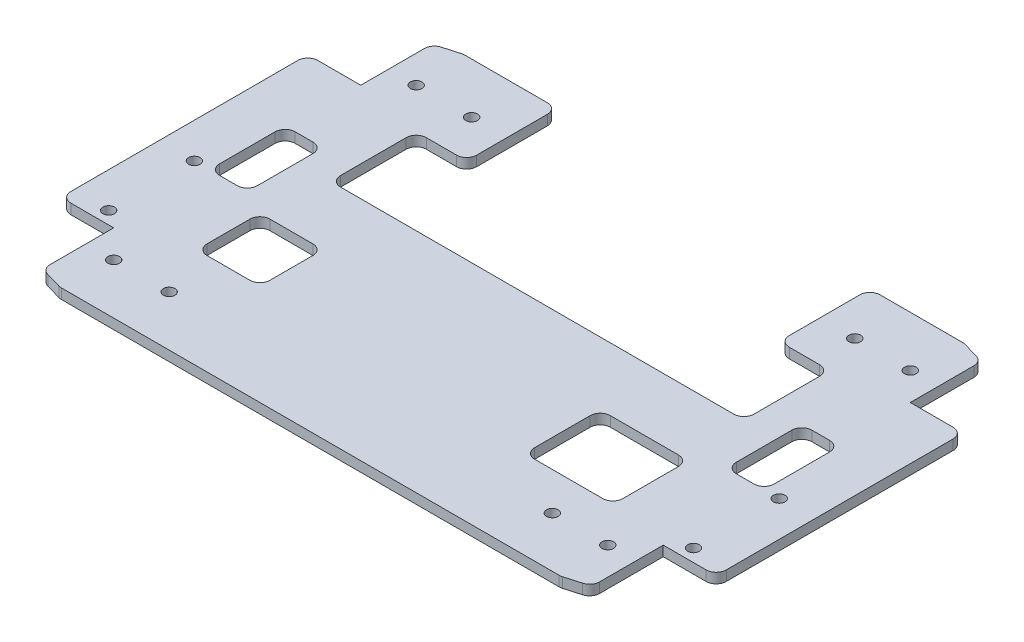
SolidWorks part; units mm, degrees
ref_plane "Plan de face" through (0, 0, 0) normal (0, 0, 1) x (1, 0, 0)
ref_plane "Plan de dessus" through (0, 0, 0) normal (0, 1, 0) x (1, 0, 0)
ref_plane "Plan de droite" through (0, 0, 0) normal (1, 0, 0) x (0, 0, -1)
sketch "Esquisse1" plane through (0, 0, 0) normal (0, 1, 0) x (1, 0, 0)
  line L0 (0, 0) -> (135, 0) construction
  line L1 (0, 0) -> (-135, 0) construction
  line L2 (-135, 0) -> (-135, -75)
  line L3 (-135, -85) -> (135, -85) construction
  line L4 (135, 0) -> (135, 75)
  line L5 (0, 85) -> (0, -85) construction
  line L6 (135, 85) -> (-135, 85) construction
  line L24 (0, -85) -> (-100, -85)
  line L26 (0, -85) -> (100, -85)
  line L28 (135, 0) -> (135, -75)
  line L31 (0, 85) -> (-100, 85)
  line L32 (0, 85) -> (100, 85)
  line L34 (-135, 0) -> (-135, 75)
  line L35 (-135, -75) -> (-100, -85)
  line L37 (-135, 75) -> (-100, 85)
  line L38 (100, 85) -> (135, 75)
  line L39 (100, -85) -> (135, -75)
  line L40 (-135, 75) -> (-100, 75) construction
  line L41 (-100, 75) -> (-100, 85) construction
  line L42 (100, -85) -> (135, -85) construction
  dimension "D2" = 270
  dimension "D4" = 200
  dimension "D8" = 170
extrude "Boss.-Extru.1" add sketch "Esquisse1" along normal blind 4
sketch "Esquisse15" plane through (0, 4, 0) normal (0, 1, 0) x (1, 0, 0)
  line L0 (-135, 60) -> (-135, 75)
  line L1 (-135, 60) -> (-120, 60) construction
  line L2 (-135, -60) -> (-120, -60) construction
  line L4 (-135, -60) -> (-135, -75)
  line L5 (-100, 85) -> (-135, 75) construction
  line L6 (-135, 75) -> (-135, -75) construction
  circle A0 centre (-120, 60) radius 2.3
  circle A1 centre (-120, -60) radius 2.3
extrude "Enlèv. mat.-Extru.6" cut sketch "Esquisse15" against normal up to next contours A1 | A0
mirror "Symétrie5" about plane through (0, 0, 0) normal (1, 0, 0) of "Enlèv. mat.-Extru.6"
sketch "Esquisse20" plane through (0, 4, 0) normal (0, 1, 0) x (1, 0, 0)
  line L0 (-120, -60) -> (-109, -60) construction
  line L1 (-109, -60) -> (-109, -82.4286)
  line L2 (-135, -75) -> (-100, -85) construction
  line L3 (-109, -60) -> (-109, -49)
  line L4 (-109, -49) -> (-135, -49)
  line L5 (-135, 75) -> (-135, -75) construction
  line L8 (-135, -49) -> (-135, -75)
  line L9 (-135, -75) -> (-109, -82.4286)
  line M49 (-135, 75) -> (-135, -75)
  line M50 (-135, -75) -> (-100, -85)
extrude "Enlèv. mat.-Extru.10" cut sketch "Esquisse20" against normal up to next contours L9 M49 M50
mirror "Symétrie7" about plane through (0, 0, 0) normal (1, 0, 0) of "Enlèv. mat.-Extru.10"
mirror "Symétrie8" about plane through (0, 0, 0) normal (0, 0, 1) of "Symétrie7", "Enlèv. mat.-Extru.10"
sketch "Esquisse26" plane through (0, 4, 0) normal (0, 1, 0) x (1, 0, 0)
  line L9 (-109, -82.4286) -> (-100, -85)
  line L14 (-100, -85) -> (-98.6264, -80.1924)
  line L16 (-109, -82.4286) -> (-107.6264, -77.621)
  line L17 (100, -85) -> (100, -80)
  line L18 (-107.6264, -77.621) -> (-98.6264, -80.1924)
  line L23 (-100, -85) -> (-100, -80)
  line L25 (-100, -80) -> (100, -80)
  line L34 (-135, -49) -> (-130, -49)
  line L35 (-109, -49) -> (-135, -49) construction
  line L47 (-107.6264, -77.621) -> (-109, -77.2285)
  line L48 (-109, -77.2285) -> (-109, -82.4286)
  line L50 (-130, -49) -> (-130, 49)
  line L53 (-109, 49) -> (-135, 49) construction
  line L54 (-130, 49) -> (-135, 49)
  line L55 (-135, 49) -> (-135, -49)
  line L56 (135, -49) -> (130, -49)
  line L57 (109, -49) -> (135, -49) construction
  line L58 (130, -49) -> (130, 49)
  line L59 (109, 49) -> (135, 49) construction
  line L60 (130, 49) -> (135, 49)
  line L61 (135, 49) -> (135, -49)
  line L63 (-109, -82.4286) -> (-109, -49) construction
  line L64 (-109, -77.2285) -> (-109, -82.4286)
  line L65 (0, -55) -> (0, 55) construction
  line L66 (109, -77.2285) -> (109, -82.4286)
  line L67 (109, -77.2285) -> (109, -82.4286)
  line L68 (107.6264, -77.621) -> (109, -77.2285)
  line L69 (100, -85) -> (100, -80)
  line L70 (107.6264, -77.621) -> (98.6264, -80.1924)
  line L71 (109, -82.4286) -> (107.6264, -77.621)
  line L72 (100, -85) -> (98.6264, -80.1924)
  line L73 (109, -82.4286) -> (100, -85)
  line L74 (-100, -85) -> (100, -85)
  line L75 (-55, 0) -> (55, 0) construction
  line L76 (100, 85) -> (-100, 85)
  line L77 (109, 82.4286) -> (100, 85)
  line L78 (100, 85) -> (98.6264, 80.1924)
  line L79 (109, 82.4286) -> (107.6264, 77.621)
  line L80 (107.6264, 77.621) -> (98.6264, 80.1924)
  line L81 (100, 85) -> (100, 80)
  line L82 (107.6264, 77.621) -> (109, 77.2285)
  line L83 (109, 77.2285) -> (109, 82.4286)
  line L84 (109, 77.2285) -> (109, 82.4286)
  line L85 (-109, 77.2285) -> (-109, 82.4286)
  line L86 (-109, 77.2285) -> (-109, 82.4286)
  line L87 (-107.6264, 77.621) -> (-109, 77.2285)
  line L88 (-100, 80) -> (100, 80)
  line L89 (-100, 85) -> (-100, 80)
  line L90 (-107.6264, 77.621) -> (-98.6264, 80.1924)
  line L91 (100, 85) -> (100, 80)
  line L92 (-109, 82.4286) -> (-107.6264, 77.621)
  line L93 (-100, 85) -> (-98.6264, 80.1924)
  line L94 (-109, 82.4286) -> (-100, 85)
  dimension "D1" = 200
  dimension "D2" = 5
  dimension "D3" = 90
  dimension "D4" = 9.3601
extrude "Enlèv. mat.-Extru.13" cut sketch "Esquisse26" against normal up to next contours L71 L66 L68 | L73 L71 L70 L25 L17 | L72 L17 L25 L70 | L14 L74 L72 L70 L25 L18 | L25 L23 L14 L18 | L23 L25 L18 L16 L9 | L47 L48 L16 | L54 L55 L34 L50 | L61 L60 L58 L56 | L82 L83 L79 | L88 L80 L79 L77 L81 | L80 L88 L81 L78 | L76 L93 L90 L88 L80 L78 | L93 L89 L88 L90 | L94 L92 L90 L88 L89 | L92 L85 L87
sketch "Esquisse27" plane through (0, 4, 0) normal (0, 1, 0) x (1, 0, 0)
  line L0 (-109, -49) -> (-130, -49) construction
  line L1 (-109, -49) -> (-109, -60) construction
  line L2 (-109, -60) -> (-98, -60) construction
  line L3 (-98, -60) -> (-76, -60) construction
  line L5 (0, -55) -> (0, 55) construction
  line L6 (98, -60) -> (76, -60) construction
  line L7 (109, -60) -> (98, -60) construction
  line L8 (109, -49) -> (109, -60) construction
  line L10 (109, -49) -> (130, -49) construction
  line L11 (-55, 0) -> (55, 0) construction
  line L12 (109, 49) -> (130, 49) construction
  line L13 (109, 49) -> (109, 60) construction
  line L14 (109, 60) -> (98, 60) construction
  line L15 (98, 60) -> (76, 60) construction
  line L16 (-98, 60) -> (-76, 60) construction
  line L17 (-109, 60) -> (-98, 60) construction
  line L18 (-109, 49) -> (-109, 60) construction
  line L19 (-109, 49) -> (-130, 49) construction
  circle A0 centre (-98, -60) radius 2.3
  circle A1 centre (-76, -60) radius 2.3
  circle A8 centre (76, -60) radius 2.3
  circle A9 centre (98, -60) radius 2.3
  circle A10 centre (98, 60) radius 2.3
  circle A11 centre (76, 60) radius 2.3
  circle A12 centre (-76, 60) radius 2.3
  circle A13 centre (-98, 60) radius 2.3
  dimension "D1" = 11
  dimension "D3" = 4.6
  dimension "D4" = 22
  dimension "D2" = 21
extrude "Enlèv. mat.-Extru.14" cut sketch "Esquisse27" against normal up to next
sketch "Esquisse28" plane through (0, 4, 0) normal (0, 1, 0) x (1, 0, 0)
  line L0 (0, 0) -> (0, 80) construction
  line L2 (-99.2997, 80) -> (99.2997, 80) construction
  line L3 (0, 80) -> (-62, 80)
  line L4 (-62, 80) -> (-62, 10)
  line L5 (-62, 10) -> (0, 10)
  line L6 (0, 10) -> (62, 10)
  line L7 (62, 10) -> (62, 80)
  line L9 (0, 80) -> (62, 80)
  dimension "D1" = 62
  dimension "D2" = 62
extrude "Enlèv. mat.-Extru.15" cut sketch "Esquisse28" against normal up to next
fillet "Congé1" radius 4 2 edges at (-62, 2, -80) (62, 2, -80)
sketch "Esquisse29" plane through (0, 4, 0) normal (0, 1, 0) x (1, 0, 0)
  line L0 (0, 0) -> (0, -15) construction
  line L1 (0, -15) -> (50, -15) construction
  line L2 (50, -15) -> (85, -15)
  line L3 (85, -15) -> (85, -45)
  line L4 (85, -45) -> (50, -45)
  line L8 (50, -15) -> (50, -45)
  line L9 (130, 0) -> (110, 0) construction
  line L10 (110, 0) -> (110, 20)
  line L19 (110, 20) -> (95, 20)
  line L20 (95, 20) -> (110, 20)
  line L21 (110, 20) -> (95, 20)
  line L22 (95, 20) -> (110, 20)
  line L23 (110, 20) -> (95, 20)
  line L24 (95, 20) -> (110, 20)
  line L25 (110, 20) -> (95, 20)
  line L26 (95, 20) -> (110, 20)
  line L27 (110, 20) -> (95, 20)
  line L28 (95, 20) -> (110, 20)
  line L29 (110, 20) -> (95, 20)
  line L30 (95, 20) -> (110, 20)
  line L31 (110, 20) -> (95, 20)
  line L32 (95, 20) -> (110, 20)
  line L33 (110, -10) -> (110, 0)
  line L34 (110, 20) -> (95, 20)
  line L35 (95, -10) -> (110, -10)
  line L36 (95, 20) -> (110, 20)
  line L37 (95, 20) -> (95, -10)
  line L49 (0, -55) -> (0, 55) construction
  line L50 (-130, 0) -> (-110, 0) construction
  line L51 (-95, 20) -> (-95, -10)
  line L52 (-95, 20) -> (-110, 20)
  line L53 (-95, -10) -> (-110, -10)
  line L54 (-110, 20) -> (-95, 20)
  line L55 (-110, -10) -> (-110, 0)
  line L56 (-95, 20) -> (-110, 20)
  line L58 (-110, 20) -> (-95, 20)
  line L60 (-95, 20) -> (-110, 20)
  line L62 (-110, 20) -> (-95, 20)
  line L64 (-95, 20) -> (-110, 20)
  line L66 (-110, 20) -> (-95, 20)
  line L68 (-95, 20) -> (-110, 20)
  line L70 (-110, 20) -> (-95, 20)
  line L72 (-95, 20) -> (-110, 20)
  line L74 (-110, 20) -> (-95, 20)
  line L76 (-95, 20) -> (-110, 20)
  line L78 (-110, 20) -> (-95, 20)
  line L80 (-95, 20) -> (-110, 20)
  line L83 (-110, 20) -> (-95, 20)
  line L84 (-110, 0) -> (-110, 20)
  line L86 (-130, 49) -> (-130, 44) construction
  line L87 (-130, -49) -> (-130, 49) construction
  line L88 (-130, 44) -> (-82, 44) construction
  line L89 (-82, 44) -> (-62, 44)
  line L90 (-62, 44) -> (-62, 10)
  line L91 (-62, 10) -> (-82, 10)
  line L92 (-82, 10) -> (-82, 44)
  line L93 (82, 10) -> (82, 44)
  line L94 (62, 10) -> (82, 10)
  line L95 (62, 44) -> (62, 10)
  line L96 (82, 44) -> (62, 44)
  line L97 (0, -15) -> (-60, -15) construction
  line L98 (-60, -15) -> (-60, -40)
  line L99 (-60, -40) -> (-85, -40)
  line L100 (-85, -40) -> (-85, -15)
  line L101 (-85, -15) -> (-60, -15)
  dimension "D1" = 50
  dimension "D2" = 35
  dimension "D5" = 48
  dimension "D6" = 20
  dimension "D7" = 34
  dimension "D8" = 5
  dimension "D9" = 25
  dimension "D10" = 60
  dimension "D11" = 25
  dimension "D12" = 20
  dimension "D13" = 20
  dimension "D14" = 30
extrude "Enlèv. mat.-Extru.16" cut sketch "Esquisse29" against normal up to next
fillet "Congé2" radius 4 22 edges at (85, 2, 15) (85, 2, 45) (50, 2, 15) (50, 2, 45) (-82, 2, -10) (-82, 2, -44) (-62, 2, -44) (82, 2, -10) (82, 2, -44) (62, 2, -44) (-60, 2, 15) (-85, 2, 40) (-60, 2, 40) (-85, 2, 15) (-110, 2, 10) (-95, 2, 10) (-95, 2, -20) (-110, 2, -20) (95, 2, 10) (110, 2, 10) (110, 2, -20) (95, 2, -20)
sketch "Esquisse30" plane through (0, 4, 0) normal (0, 1, 0) x (1, 0, 0)
  line L0 (-130, -49) -> (-130, -27) construction
  line L1 (-130, -49) -> (-130, 49) construction
  line L2 (-130, -27) -> (-116, -27) construction
  line L3 (-116, -27) -> (-116, -44) construction
  line L4 (-116, -27) -> (-116, -10) construction
  line L5 (0, -55) -> (0, 55) construction
  line L6 (116, -27) -> (116, -10) construction
  line L7 (116, -27) -> (116, -44) construction
  line L8 (130, -27) -> (116, -27) construction
  line L9 (130, -49) -> (130, -27) construction
  circle A0 centre (-116, -44) radius 2.3
  circle A1 centre (-116, -10) radius 2.3
  circle A2 centre (116, -44) radius 2.3
  circle A3 centre (116, -10) radius 2.3
  dimension "D1" = 14
  dimension "D2" = 22
extrude "Enlèv. mat.-Extru.17" cut sketch "Esquisse30" against normal up to next
fillet "Congé3" radius 4 12 edges at (99.2997, 2, 80) (109, 2, 77.2285) (130, 2, 49) (130, 2, -49) (109, 2, -77.2285) (99.2997, 2, -80) (-99.2997, 2, -80) (-109, 2, -77.2285) (-130, 2, -49) (-130, 2, 49) (-109, 2, 77.2285) (-99.2997, 2, 80)
